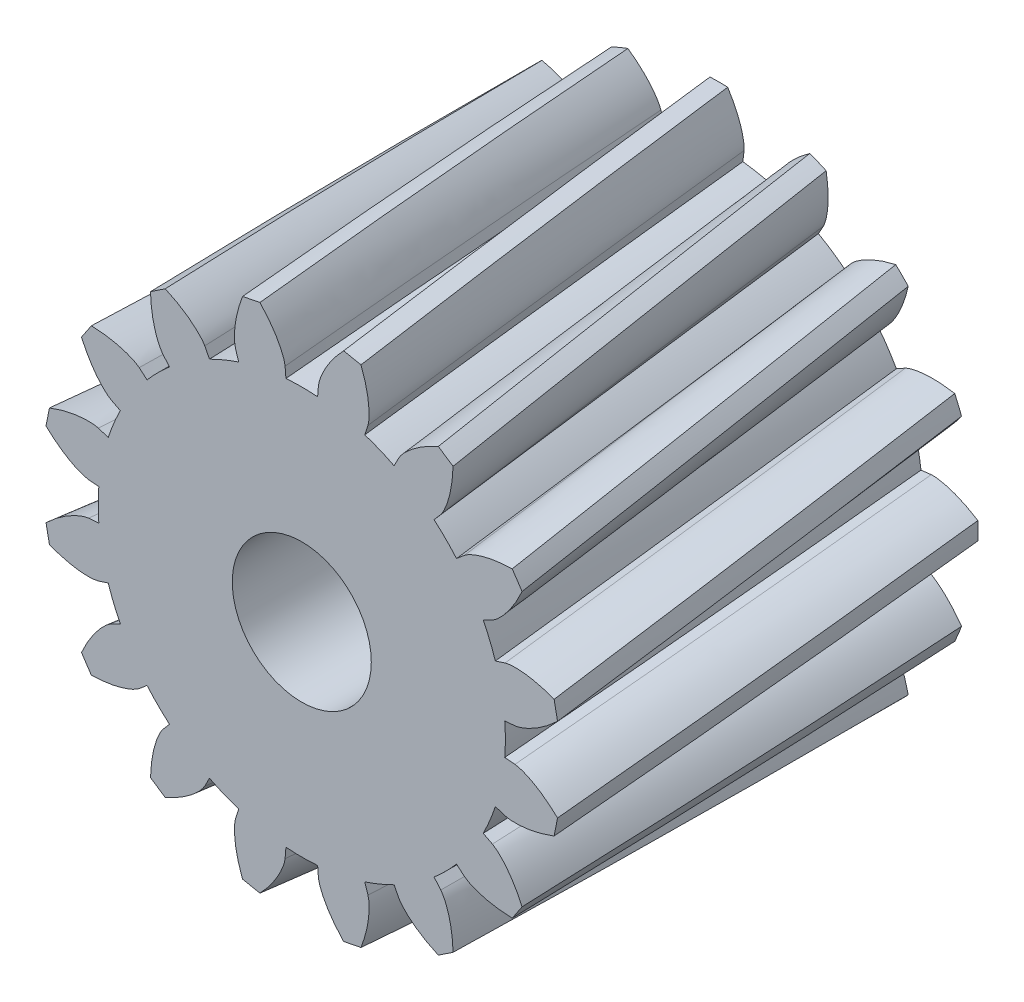
SolidWorks part; units mm, degrees
material "ABS"
ref_plane "Front Plane" through (0, 0, 0) normal (0, 0, 1) x (1, 0, 0)
ref_plane "Top Plane" through (0, 0, 0) normal (0, 1, 0) x (1, 0, 0)
ref_plane "Right Plane" through (0, 0, 0) normal (1, 0, 0) x (0, 0, -1)
sketch "Definition Drawing" plane through (0, 0, 0) normal (0, 0, 1) x (1, 0, 0)
  line L0 (5.593, 0) -> (4.593, 0) construction
  line L1 (0, 0) -> (-2.475, 3.8962) construction
  line L2 (0, 0) -> (0, 5.593) construction
  line L3 (0, 0) -> (0.545, 4.5835) construction
  line L4 (-2.475, 3.8962) -> (0.191, 5.5897) construction
  line L5 (0, 0) -> (0.4494, 5.0731) construction
  line L6 (0, 0) -> (0.4992, 5.0684) construction
  line L7 (0, 0) -> (-1.7756, 4.2606) construction
  line L8 (-1.7756, 4.2606) -> (0.411, 5.1718) construction
  line L9 (0, 0) -> (-1.0244, 4.5007) construction
  line L10 (-1.0244, 4.5007) -> (0.5155, 4.8512) construction
  line L11 (0, 0) -> (-0.2433, 4.6094) construction
  line L12 (-0.2433, 4.6094) -> (0.5453, 4.651) construction
  circle A0 centre (0, 0) radius 4.6158 construction
  circle A1 centre (0, 0) radius 4.593 construction
  circle A2 centre (0, 0) radius 5.093 construction
  circle A3 centre (0, 0) radius 5.593 construction
  circle A4 centre (0, 0) radius 4.393 construction
  arc A5 (0.4494, 5.0731) -> (0.4992, 5.0684) centre (0, 0) cw construction
  spline S0 degree 3 poles (0.545, 4.5835) (0.5498, 4.6736) (0.4942, 5.0324) (0.3345, 5.3618) (0.191, 5.5897) knots 0 0 0 0 0.250023 1 1 1 1 construction
  point P13 (5.093, 0)
  dimension "D4" = 10.1859
  dimension "D5" = 9.2316
  dimension "D1" = 1
  dimension "D2" = 0.2
  dimension "D3" = 5.625
  dimension "D6" = 0.05
  dimension "D7" = 39.206
  dimension "D11" = 2.3688
  dimension "D12" = 1.5792
  dimension "D13" = 0.7896
  dimension "D8" = 29.404
  dimension "D9" = 19.603
  dimension "D10" = 9.801
sketch "Sketch5" plane through (0, 0, 0) normal (0, 0, 1) x (1, 0, 0)
  circle A1 centre (0, 0) radius 4.393
  circle A2 centre (0, 0) radius 1.5
  circle A3 centre (0, 0) radius 4.393 construction
  dimension "D1" = 3
extrude "Extrude Body" add sketch "Sketch5" along normal blind 9
sketch "Sketch7" plane through (0, 0, 0) normal (0, 0, 1) x (1, 0, 0)
  circle A0 centre (0, 0) radius 4.393
  circle A1 centre (0, 0) radius 4.393 construction
curve "Tooth Helix" pitch 288 height 9 turns 0.0312
sketch "Sketch6" plane through (0, 0, 0) normal (0, 0, 1) x (1, 0, 0)
  line L0 (0, 5.593) -> (0, 0) construction
  line L4 (0.545, 4.5835) -> (0.1771, 1.4895)
  line L5 (0, 0) -> (0.545, 4.5835) construction
  line L6 (-0.545, 4.5835) -> (-0.1771, 1.4895)
  arc A0 (0.191, 5.5897) -> (-0.191, 5.5897) centre (0, 0) ccw
  arc A3 (0.1771, 1.4895) -> (-0.1771, 1.4895) centre (0, 0) ccw
  circle A4 centre (0, 0) radius 1.5 construction
  spline S0 degree 3 poles (0.545, 4.5835) (0.5498, 4.6736) (0.4942, 5.0324) (0.3345, 5.3618) (0.191, 5.5897) knots 0 0 0 0 0.250023 1 1 1 1
  spline S1 degree 3 poles (-0.545, 4.5835) (-0.5498, 4.6736) (-0.4942, 5.0324) (-0.3345, 5.3618) (-0.191, 5.5897) knots 0 0 0 0 0.250023 1 1 1 1
sweep "Sweep Half Tooth" add profiles "Sketch6" path "Tooth Helix"
pattern_circular "Pattern Half Teeth" count 16 over 360 about axis through (0, 0, 9) along (0, 0, -1) of "Sweep Half Tooth"
sketch "Sketch8" plane through (0, 0, 0) normal (0, 0, 1) x (1, 0, 0)
  line L6 (0, 5.593) -> (0, 0) construction
  line L7 (0, 0) -> (0, 5.593) construction
  line L8 (1.5, 5.8839) -> (1.5, 4.899)
  line L9 (-1.5, 4.899) -> (-1.5, 5.8839)
  circle A2 centre (0, 0) radius 5.593 construction
  arc A20 (-2.8911, 6.8042) -> (2.8911, 6.8042) centre (0, 0) ccw
  circle A21 centre (0, 0) radius 4.393 construction
  arc A23 (-1.5, 5.8839) -> (-2.8911, 6.8042) centre (-2.5, 5.8839) ccw
  arc A24 (-1.5, 4.899) -> (-2.0455, 4.0083) centre (-2.5, 4.899) cw
  arc A25 (1.5, 4.899) -> (2.0455, 4.0083) centre (2.5, 4.899) ccw
  arc A26 (1.5, 5.8839) -> (2.8911, 6.8042) centre (2.5, 5.8839) cw
  arc A27 (-2.0455, 4.0083) -> (2.0455, 4.0083) centre (0, 0) ccw
  circle A28 centre (0, 0) radius 1.5 construction
  dimension "D1" = 3
  dimension "D6" = 1
  dimension "D4" = 3
  dimension "D5" = 3
  dimension "D2" = 3
  dimension "D3" = 180
extrude "Cut Spoke" [suppressed] cut sketch "Sketch8" against normal through all and the other way through all
pattern_circular "Pattern Spokes" [suppressed] count 2 over 360
mirror "Mirror Body" [suppressed] about plane through (0, 0, 0) normal (0, 0, 1)
equation "\"nTeeth\" = 16"
equation "\"xThickness\"= 18"
equation "\"dShaft\"= 3"
equation "\"aPressure\"=25"
equation "\"pitch\"= 2"
equation "\"rHeight\"= 1"
equation "\"rClearance\"= 0.2"
equation "\"xClearance\"=0.05"
equation "\"rFillet\"= 1"
equation "\"nSpokes\"= int ( ( \"nTeeth\" - 1 ) / 10 ) + 1'rounds up"
equation "\"dPitch\"= \"nTeeth\" * \"pitch\" / pi"
equation "\"xWall\"= IIF ( \"nTeeth\" > 30 , \"nTeeth\" / 10 , 3 )"
equation "\"dBase\"= \"dPitch\" * cos ( \"aPressure\" )"
equation "\"rOuter\"= \"dPitch\" / 2 + \"rHeight\" / 2"
equation "\"xInvolute\"= sqr ( \"rOuter\" ^ 2 - ( \"dBase\" / 2 ) ^ 2 )"
equation "\"aInvolute\"= 360 * \"xInvolute\" / ( \"dBase\" / 2 ) / 2 / pi"
equation "\"xSkew\"= 1"
equation "\"D1@Definition Drawing\" = \"rHeight\""
equation "\"D2@Definition Drawing\" = \"rClearance\""
equation "\"D4@Definition Drawing\" = \"dPitch\""
equation "\"D6@Definition Drawing\" = \"xClearance\""
equation "\"D5@Definition Drawing\" = \"dBase\""
equation "\"D7@Definition Drawing\" = \"aInvolute\""
equation "\"D11@Definition Drawing\" = \"xInvolute\" * 0.75"
equation "\"D12@Definition Drawing\" = \"xInvolute\" * 0.5"
equation "\"D13@Definition Drawing\" = \"xInvolute\" * 0.25"
equation "\"D8@Definition Drawing\" = \"aInvolute\" * 0.75"
equation "\"D9@Definition Drawing\" = \"aInvolute\" * 0.5"
equation "\"D10@Definition Drawing\" = \"aInvolute\" * 0.25"
equation "\"D1@Extrude Body\"=\"xThickness\"/2"
equation "\"D1@Sketch5\"=\"dShaft\""
equation "\"D5@Tooth Helix\" = \"xSkew\" /  ( \"dPitch\" * pi ) "
equation "\"D3@Tooth Helix\" = \"xThickness\" / 2"
equation "\"D7@Tooth Helix\" = 90.00deg"
equation "\"D3@Definition Drawing\" = 360 / \"nTeeth\" / 2 / 2"
equation "\"D5@Sketch8\"=\"xWall\""
equation "\"D1@Sketch8\"=\"xWall\""
equation "\"D4@Sketch8\"=\"xWall\""
equation "\"D6@Sketch8\"=\"rFillet\""
equation "\"D1@Pattern Spokes\" = \"nSpokes\""
equation "\"rHub\"= IIF ( \"xWall\" * \"nSpokes\" / 6 > \"xWall\" , \"xWall\" * \"nSpokes\" / 6 , \"xWall\" )"
equation "\"D1@Pattern Half Teeth\" = \"nTeeth\""
equation "\"D2@Sketch8\"=\"rHub\""
equation "\"D3@Sketch8\"=360/\"nSpokes\""
